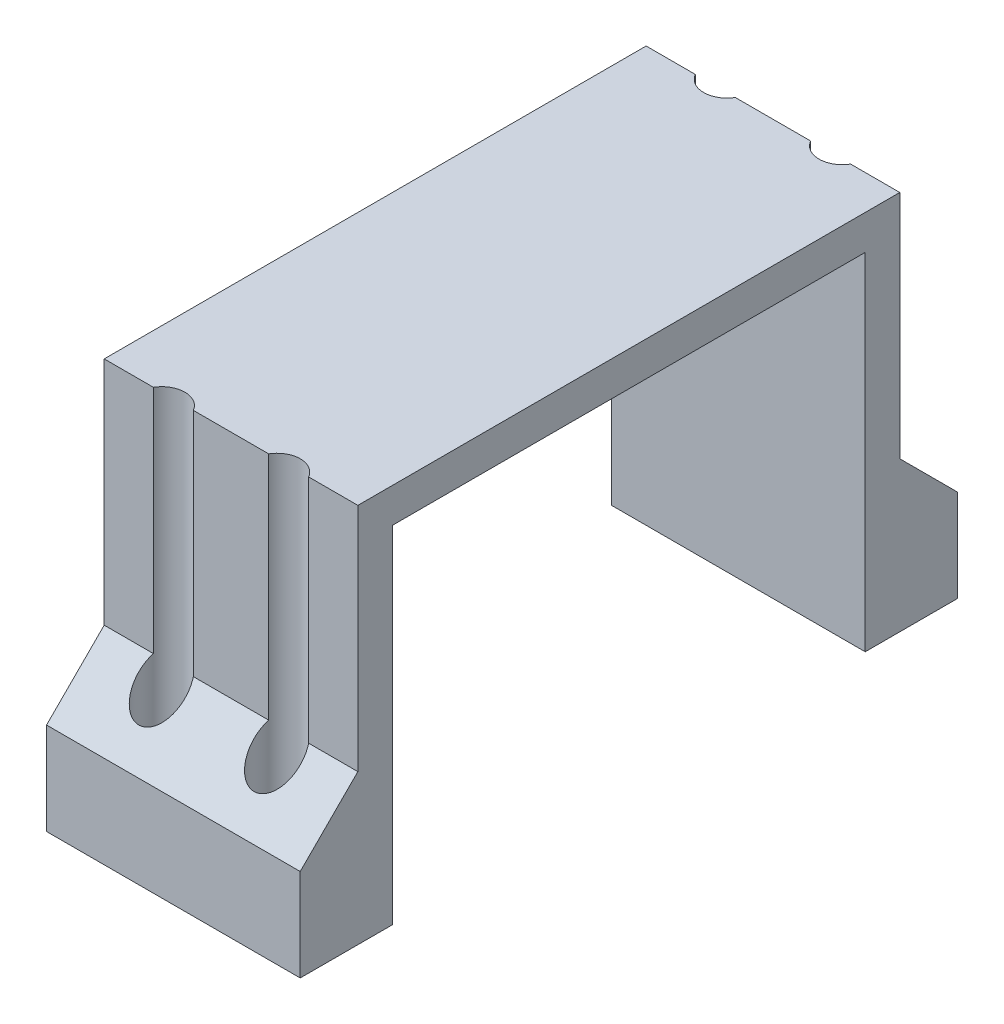
SolidWorks part; units mm, degrees
ref_plane "Alzado" through (0, 0, 0) normal (0, 0, 1) x (1, 0, 0)
ref_plane "Planta" through (0, 0, 0) normal (0, 1, 0) x (1, 0, 0)
ref_plane "Vista lateral" through (0, 0, 0) normal (1, 0, 0) x (0, 0, -1)
sketch "Croquis1" plane through (0, 0, 0) normal (0, 1, 0) x (1, 0, 0)
  line L1 (-11, 23.5) -> (11, 23.5)
  line L2 (-11, 23.5) -> (-11, -23.5)
  line L3 (-11, -23.5) -> (11, -23.5)
  line L4 (11, 23.5) -> (11, -23.5)
  line L5 (-11, 23.5) -> (11, -23.5) construction
  line L6 (-11, -23.5) -> (11, 23.5) construction
  point P0 (0, 0)
  dimension "D1" = 47
  dimension "D2" = 22
extrude "Saliente-Extruir1" add sketch "Croquis1" along normal blind 3
sketch "Croquis2" plane through (0, 0, 0) normal (0, -1, 0) x (1, 0, 0)
  line L0 (-11, 23.5) -> (-11, 20.5)
  line L1 (-11, -23.5) -> (-11, 23.5) construction
  line L2 (-11, 20.5) -> (11, 20.5)
  line L3 (11, 23.5) -> (11, -23.5) construction
  line L4 (11, 20.5) -> (11, 23.5)
  line L5 (11, 23.5) -> (-11, 23.5)
  line L6 (-28.3497, 0) -> (28.3497, 0) construction
  line L7 (11, -23.5) -> (-11, -23.5)
  line L8 (11, -20.5) -> (11, -23.5)
  line L9 (-11, -20.5) -> (11, -20.5)
  line L10 (-11, -23.5) -> (-11, -20.5)
  point P13 (0, 0)
  dimension "D1" = 3
extrude "Saliente-Extruir2" add sketch "Croquis2" along normal blind 30
sketch "Croquis4" plane through (0, 0, 0) normal (1, 0, 0) x (0, 0, -1)
  line L0 (23.5, -30) -> (28.5, -30)
  line L1 (28.5, -30) -> (28.5, -22)
  line L2 (28.5, -22) -> (23.5, -17)
  line L3 (23.5, 3) -> (23.5, -30) construction
  line L5 (23.5, -17) -> (23.5, -30)
  dimension "D1" = 5
  dimension "D2" = 8
  dimension "D3" = 135
extrude "Saliente-Extruir3" add sketch "Croquis4" along normal up to vertex (11 mm away) and the other way up to vertex (11 mm away)
sketch "Croquis5" plane through (0, -30, 0) normal (0, -1, 0) x (1, 0, 0)
  line L0 (0, 0) -> (0, -38.2203) construction
  line L1 (-28.3033, 0) -> (28.3033, 0) construction
  circle A0 centre (5, -24.5) radius 2
  circle A2 centre (-5, -24.5) radius 2
  point P8 (0, 0)
  dimension "D1" = 24.5
  dimension "D2" = 4
  dimension "D3" = 5
extrude "Cortar-Extruir1" cut sketch "Croquis5" against normal through all both and the other way through all
mirror "Simetría1" about plane through (0, 0, 0) normal (0, 0, 1) of "Cortar-Extruir1", "Saliente-Extruir3"
